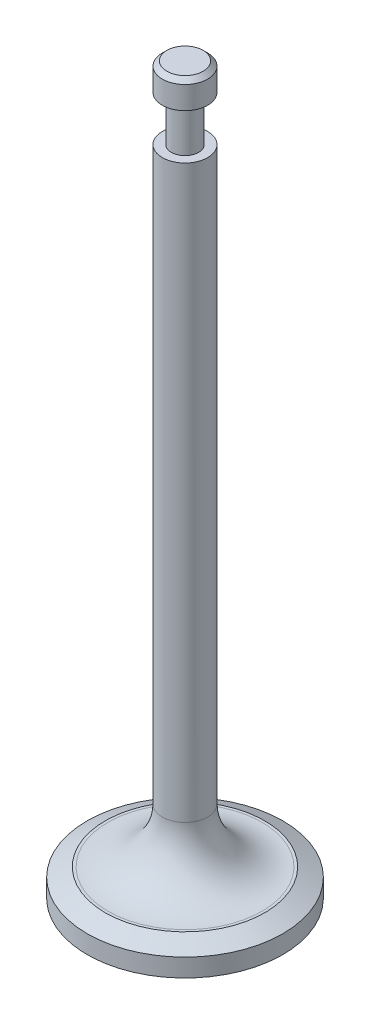
SolidWorks part; units mm, degrees
ref_plane "Front Plane" through (0, 0, 0) normal (0, 0, 1) x (1, 0, 0)
ref_plane "Top Plane" through (0, 0, 0) normal (0, 1, 0) x (1, 0, 0)
ref_plane "Right Plane" through (0, 0, 0) normal (1, 0, 0) x (0, 0, -1)
sketch "Sketch1" plane through (0, 0, 0) normal (0, 0, 1) x (1, 0, 0)
  line L0 (0, 0) -> (0, 80)
  line L1 (0, 80) -> (2.5, 80)
  line L2 (2.5, 80) -> (2.5, 77)
  line L3 (2.5, 77) -> (1.5, 77)
  line L4 (1.5, 77) -> (1.5, 72)
  line L5 (1.5, 72) -> (2.5, 72)
  line L6 (2.5, 72) -> (2.5, 3)
  line L7 (2.5, 3) -> (10.7931, 3)
  line L8 (10.7931, 3) -> (10.7931, 0)
  line L9 (10.7931, 0) -> (0, 0)
  dimension "D1" = 1
  dimension "D2" = 80
  dimension "D3" = 3
  dimension "D4" = 10.7931
  dimension "D5" = 3
  dimension "D6" = 2.5
  dimension "D7" = 5
revolve "Revolve1" add sketch "Sketch1" angle 360 about L0
fillet "Fillet1" radius 6 1 edges at (0, 3, -2.5)
chamfer "Chamfer1" distance 0.5 angle 45 1 edges at (0, 80, -2.5)
chamfer "Chamfer2" distance 2 distance2 1 1 edges at (0, 3, -10.7931)
